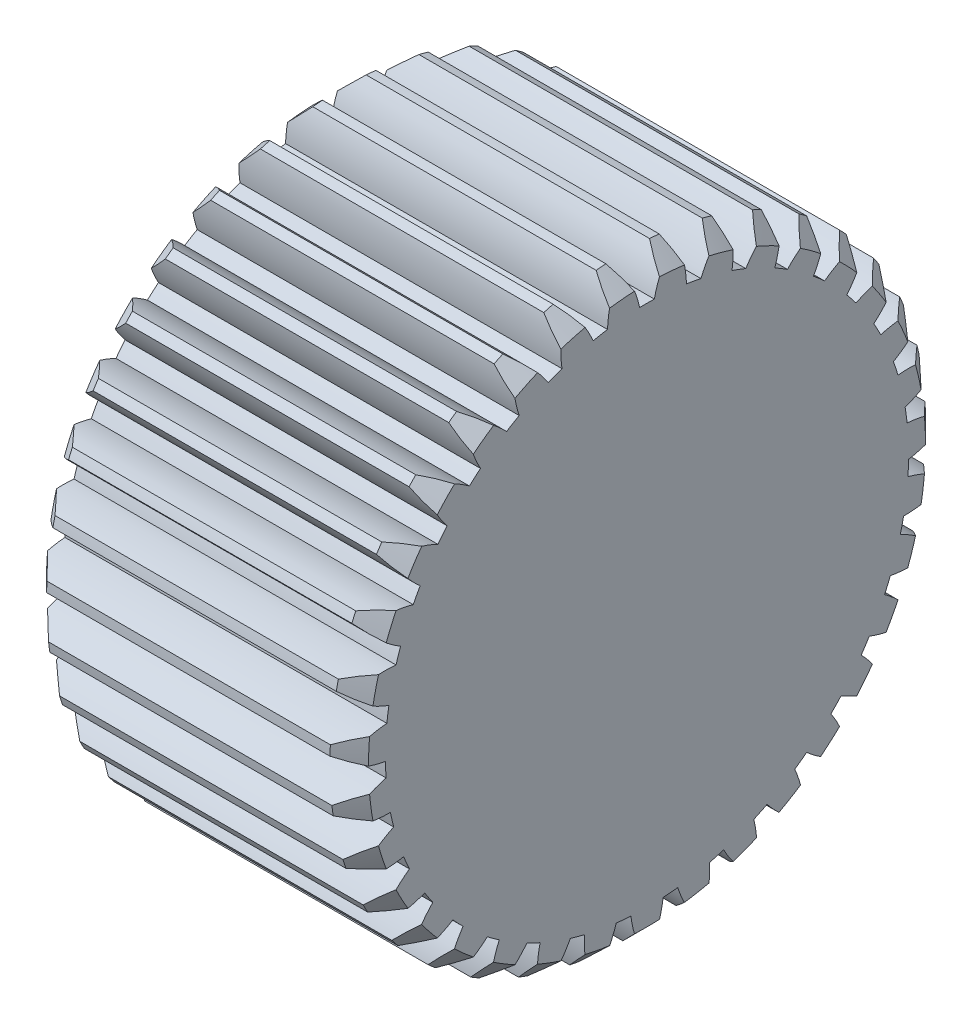
SolidWorks part; units mm, degrees
ref_plane "Plane1" through (0, 0, 0) normal (0, 0, 1) x (1, 0, 0)
ref_plane "Plane2" through (0, 0, 0) normal (0, 1, 0) x (1, 0, 0)
ref_plane "Plane3" through (0, 0, 0) normal (1, 0, 0) x (0, 0, -1)
sketch "HoldingSke" plane through (0, 0, 0) normal (0, 1, 0) x (1, 0, 0)
  line L0 (0, 0) -> (1.6383, -1.1472)
  line L1 (-15, 0) -> (100, 0) construction
  line L2 (0, 0) -> (-2.1039, 2.3779)
  line L3 (0, 0) -> (-11.863, 4.5341)
  line L4 (0, 0) -> (7.0742, 4.9534)
  line L5 (0, 0) -> (-46.8476, -17.4728)
  line L6 (0, 0) -> (-8.2896, -5.593)
  line L7 (-2.1039, 2.3779) -> (8.6586, 51.2059)
  line L8 (-76.2, 54.61) -> (-75.3, 54.61)
  line L9 (-71.009, 38.7566) -> (-53.1078, 45.2721)
  line L10 (-76.2, 71.12) -> (104.1128, 71.12)
  line L11 (0, 0) -> (-10, 0)
  line L12 (-76.2, 101.6) -> (-76.181, 101.6)
  line L13 (24.9733, 27.94) -> (52.9518, 28.4284)
  line L14 (24.9733, 27.94) -> (24.9743, 27.94)
  line L15 (24.9733, 27.94) -> (100.4006, 29.5858)
  line L16 (-63.627, -0.5) -> (-12.827, -0.5)
  circle A0 centre (0, 0) radius 2.5
  circle A1 centre (0, 0) radius 8.124
  circle A2 centre (0, 0) radius 37.5
  circle A3 centre (0, 0) radius 2.5
  dimension "MHD" = 16.248
  dimension "Hub_dia" = 75
  dimension "Bore" = 5
  dimension "MBD" = 5
  dimension "Num_teeth" = 35
  dimension "Pitch" = 2
  dimension "Overall_len" = 50
  dimension "Show_teeth" = 35
  dimension "Thickness" = 10
  dimension "OAL" = 50.0001
  dimension "T_dim" = 0.9
  dimension "Ap" = 20
  dimension "H" = 19.05
  dimension "Pitch_radius" = 180.3128
  dimension "Width" = 10
  dimension "Backlash" = 0.019
  dimension "Addendum_fac" = 1
  dimension "Dedendum_fac" = 1.25
  dimension "Clearance_fac" = 0.25
  dimension "Dedendum_add" = 0.001
  dimension "Module" = 0.5
sketch "BasProSke" plane through (0, 0, 0) normal (0, 1, 0) x (1, 0, 0)
  line L0 (-10, 0) -> (60, 0) construction
  line L1 (0, 0) -> (0, 9.25)
  line L2 (0, 0) -> (10, 0)
  line L3 (10, 0) -> (10, 9.25)
  line L4 (10, 9.25) -> (0, 9.25)
  dimension "Thickness" = 10
  dimension "Diameter" = 18.5
revolve "Base-Revolve" add sketch "BasProSke" angle 360 about L0
sketch "TooCutSke" plane through (0, 0, 0) normal (1, 0, 0) x (0, 0, -1)
  line L1 (0, 0) -> (0, 107) construction
  line L2 (0, 0) -> (-0.4258, 8.7396) construction
  line L3 (0, 0) -> (-1.5674, 17.4148) construction
  line L4 (-0.4258, 8.7396) -> (-0.7837, 8.7074) construction
  arc A0 (0.2281, 8.1208) -> (-0.2281, 8.1208) centre (0, 0) ccw
  arc A1 (0.6942, 9.2494) -> (-0.6942, 9.2494) centre (0, 0) ccw
  circle A2 centre (0, 0) radius 8.75 construction
  circle A3 centre (0, 0) radius 8.2223 construction
  arc A4 (-0.2281, 8.1208) -> (-0.6942, 9.2494) centre (-3.6465, 7.3695) ccw
  arc A5 (0.6942, 9.2494) -> (0.2281, 8.1208) centre (3.6465, 7.3695) ccw
  dimension "Root_dia" = 16.248
  dimension "Overcut_dia" = 18.5508
  dimension "Pitch_dia" = 17.5
  dimension "Base_dia" = 16.4446
  dimension "Flank_rad" = 3.5
  dimension "Half_ang" = 5.143
  dimension "Half_CT" = 0.3593
extrude "ToothCut" cut sketch "TooCutSke" along normal through all
fillet "Breaks" [suppressed] radius 0.01
fillet "RootFillets" [suppressed] radius 0.126
pattern_circular "TeethCuts" count 35 every 10.286 about axis through (-10, 0, 0) along (1, 0, 0) of "ToothCut", "RootFillets", "Breaks"
sketch "HubNeaOneSke" plane through (0, 0, 0) normal (-1, 0, 0) x (0, 0, 1)
  circle A0 centre (0, 0) radius 8.124
  dimension "Diameter" = 16.248
extrude "HubNearOne" [suppressed] add sketch "HubNeaOneSke" along normal blind 40.0001
sketch "HubNeaBotSke" plane through (0, 0, 0) normal (-1, 0, 0) x (0, 0, 1)
  circle A0 centre (0, 0) radius 8.124
  dimension "Diameter" = 16.248
extrude "HubNearBoth" [suppressed] add sketch "HubNeaBotSke" along normal blind 20
ref_plane "FarPln" through (10, 0, 0) normal (1, 0, 0) x (0, 0, -1)
sketch "HubFarSke" plane through (10, 0, 0) normal (1, 0, 0) x (0, 0, -1)
  circle A0 centre (0, 0) radius 8.124
  dimension "Diameter" = 16.248
extrude "HubFar" [suppressed] add sketch "HubFarSke" along normal blind 20
sketch "BorSke" plane through (0, 0, 0) normal (1, 0, 0) x (0, 0, -1)
  circle A0 centre (0, 0) radius 2.5
  dimension "Diameter" = 5
extrude "Bore" cut sketch "BorSke" along normal mid plane 100.0001
sketch "KeySke" plane through (0, 0, 0) normal (1, 0, 0) x (0, 0, -1)
  line L0 (-1, 0) -> (-1, 3.4)
  line L1 (-1, 3.4) -> (1, 3.4)
  line L2 (1, 3.4) -> (1, 0)
  line L3 (0, 0) -> (0, 34) construction
  line L4 (-1, 0) -> (1, 0)
  dimension "Offset" = 3.4
  dimension "Width" = 2
extrude "Keyway" [suppressed] cut sketch "KeySke" along normal mid plane 100.0001
pattern_circular "Keyway2" [suppressed] count 2 every 90 about axis through (-10, 0, 0) along (1, 0, 0)
sketch "Sketch1" plane through (0, 0, 0) normal (0, 1, 0) x (1, 0, 0)
  line L0 (0, 9.25) -> (0.6, 9.25)
  line L1 (0.6, 9.25) -> (0, 8.65)
  line L2 (0, 8.65) -> (0, 9.25)
  line L3 (5, 9.2462) -> (5, 14.8117) construction
  line L4 (0, 9.2462) -> (10, 9.2462) construction
  line L5 (0, 0) -> (-11.762, 0) construction
  line L6 (0, 0.2281) -> (0, -0.2281) construction
  line L7 (10, 8.65) -> (10, 9.25)
  line L8 (9.4, 9.25) -> (10, 8.65)
  line L9 (10, 9.25) -> (9.4, 9.25)
  line L10 (0, 8.9833) -> (0, 7.7938) construction
  dimension "D1" = 9.25
  dimension "D2" = 0.6
revolve "Cut-Revolve1" cut sketch "Sketch1" angle 360 about L5
sketch "Sketch2" plane through (0, 0, 0) normal (-1, 0, 0) x (0, 0, 1)
  circle A0 centre (0, 0) radius 2.5
extrude "Boss-Extrude1" add sketch "Sketch2" against normal up to surface (10 mm away) up to face at (10, 0, 2.5)
sketch "Sketch3" plane through (0, 0, 0) normal (-1, 0, 0) x (0, 0, 1)
  line L0 (-5.9453, -2.1528) -> (5.9453, -2.1528) construction
  text T0 "35" font "Century Gothic" height 5
  point P2 (0, -2.1528)
extrude "Cut-Extrude1" cut sketch "Sketch3" against normal blind 0.5
equation "' \"Module@HoldingSke\" = 6.35"
equation "' \"Num_teeth@HoldingSke\" = 12"
equation "' \"Ap@HoldingSke\" =  20"
equation "' \"Ap@HoldingSke\" = 20"
equation "' \"Width@HoldingSke\" = 0.5 * 25.4"
equation "' \"Hub_dia@HoldingSke\"= 1 * 25.4"
equation "' \"Hub_dia@HoldingSke\" = 1 * 25.4"
equation "' \"Overall_len@HoldingSke\" = 1.0 * 25.4"
equation "' \"Bore@HoldingSke\" = 0.75 * 25.4"
equation "' \"T_dim@HoldingSke\" = 0.1 * 25.4"
equation "' \"Width@KeySke\" = 0.25 * 25.4"
equation "' \"Show_teeth@HoldingSke\" = 13"
equation "' \"Backlash@HoldingSke\" = 0.009 * 25.4"
equation "' \"Addendum_fac@HoldingSke\" = 1.0"
equation "' \"Dedendum_fac@HoldingSke\" = 1.25"
equation "' \"Dedendum_add@HoldingSke\" = 0.00005 * 25.4"
equation "' \"Clearance_fac@HoldingSke\" = 0.25"
equation "\"Pitch@HoldingSke\" = 1 / \"Module@HoldingSke\""
equation "\"Overcut_dia@TooCutSke\" = (\"Num_teeth@HoldingSke\" + 2 * \"Addendum_fac@HoldingSke\") / \"Pitch@HoldingSke\" + 0.002 * 25.4"
equation "\"Pitch_dia@TooCutSke\" = \"Num_teeth@HoldingSke\" / \"Pitch@HoldingSke\""
equation "\"Base_dia@TooCutSke\" = \"Num_teeth@HoldingSke\" / \"Pitch@HoldingSke\" * cos((\"Ap@HoldingSke\"  * 3.14159265 / 180))"
equation "\"Root_dia@TooCutSke\" = (\"Num_teeth@HoldingSke\" + 2) / \"Pitch@HoldingSke\" - 2 * (\"Addendum_fac@HoldingSke\" + \"Dedendum_fac@HoldingSke\") / \"Pitch@HoldingSke\" - \"Dedendum_add@HoldingSke\" * 2"
equation "\"Half_ang@TooCutSke\" = 180 / \"Num_teeth@HoldingSke\""
equation "\"Half_CT@TooCutSke\" = \"Num_teeth@HoldingSke\" / \"Pitch@HoldingSke\" * sin((3.14159265 / 2 / \"Num_teeth@HoldingSke\")) / 2 - 7 * \"Backlash@HoldingSke\" / 4"
equation "\"Flank_rad@TooCutSke\" = \"Num_teeth@HoldingSke\" / \"Pitch@HoldingSke\" / 5"
equation "\"Radius@RootFillets\" = \"Clearance_fac@HoldingSke\" / \"Pitch@HoldingSke\" + \"Dedendum_add@HoldingSke\""
equation "\"Break_rad@Breaks\" = 0.02 / \"Pitch@HoldingSke\""
equation "\"Thickness@HoldingSke\" = \"Width@HoldingSke\""
equation "\"OAL@HoldingSke\" = \"Thickness@HoldingSke\""
equation "\"MHD@HoldingSke\" = (\"Num_teeth@HoldingSke\" + 2) / \"Pitch@HoldingSke\" - 2 * (\"Addendum_fac@HoldingSke\" + \"Dedendum_fac@HoldingSke\")  / \"Pitch@HoldingSke\" - \"Dedendum_add@HoldingSke\" * 2"
equation "\"MBD@HoldingSke\" = (\"Num_teeth@HoldingSke\" + 2) / \"Pitch@HoldingSke\" - 2 * (\"Addendum_fac@HoldingSke\" + \"Dedendum_fac@HoldingSke\")  / \"Pitch@HoldingSke\" - \"Dedendum_add@HoldingSke\" * 2 - 0.002 * 25.4"
equation "\"MHD@HoldingSke\" = ((sgn( \"MHD@HoldingSke\" - \"Hub_dia@HoldingSke\" )-1)*( \"MHD@HoldingSke\" - \"Hub_dia@HoldingSke\" ))/-2+ \"Hub_dia@HoldingSke\""
equation "\"MBD@HoldingSke\" = ((sgn( \"MBD@HoldingSke\" - \"Bore@HoldingSke\" )-1)*( \"MBD@HoldingSke\" - \"Bore@HoldingSke\" ))/-2+ \"Bore@HoldingSke\""
equation "\"OAL@HoldingSke\" = ((sgn( \"OAL@HoldingSke\" - \"Overall_len@HoldingSke\" )+1)*( \"OAL@HoldingSke\" - \"Overall_len@HoldingSke\" ))/2 + \"Overall_len@HoldingSke\" + 0.000002 * 25.4"
equation "\"Num_teeth@TeethCuts\" = int( \"Show_teeth@HoldingSke\" ) + 1"
equation "\"Num_teeth@TeethCuts\" = ((sgn( \"Num_teeth@TeethCuts\" - \"Num_teeth@HoldingSke\" )-1)*( \"Num_teeth@TeethCuts\" - \"Num_teeth@HoldingSke\" ))/-2+ \"Num_teeth@HoldingSke\""
equation "\"Num_teeth@TeethCuts\" = ((sgn( \"Num_teeth@TeethCuts\" - 2.0)+1)*( \"Num_teeth@TeethCuts\" - 2.0))/2 +2.0"
equation "\"Angle@TeethCuts\" = 360.0 / \"Num_teeth@HoldingSke\""
equation "\"Diameter@BasProSke\" = (\"Num_teeth@HoldingSke\" + 2 * \"Addendum_fac@HoldingSke\") / \"Pitch@HoldingSke\""
equation "\"Thickness@BasProSke\"  = \"Thickness@HoldingSke\""
equation "' \"Fillet_rad@BasProSke\" =  \"Thickness@HoldingSke\" * 0.05"
equation "' \"Fillet_rad@BasProSke\" = \"Thickness@HoldingSke\" * 0.05"
equation "\"MHD@HoldingSke\" = ((sgn( \"MHD@HoldingSke\" - \"Root_dia@TooCutSke\" )-1)*( \"MHD@HoldingSke\" - \"Root_dia@TooCutSke\" ))/-2+ \"Root_dia@TooCutSke\""
equation "\"Diameter@HubNeaOneSke\" = \"MHD@HoldingSke\""
equation "\"Length@HubNearOne\" = \"OAL@HoldingSke\" - \"Thickness@BasProSke\""
equation "\"Diameter@HubNeaBotSke\" = \"MHD@HoldingSke\""
equation "\"Length@HubNearBoth\" = ( \"OAL@HoldingSke\" - \"Thickness@BasProSke\" ) / 2.0"
equation "\"Thickness@FarPln\" = \"Thickness@BasProSke\""
equation "\"Diameter@HubFarSke\" = \"MHD@HoldingSke\""
equation "\"Length@HubFar\" = ( \"OAL@HoldingSke\" - \"Thickness@BasProSke\" ) / 2.0"
equation "\"Diameter@BorSke\" = \"MBD@HoldingSke\""
equation "\"D1@Bore\" = \"OAL@HoldingSke\" * 2.0"
equation "\"D1@Keyway\" = \"OAL@HoldingSke\" * 2.0"
equation "\"Offset@KeySke\" = \"T_dim@HoldingSke\" + \"MBD@HoldingSke\" / 2.0"
